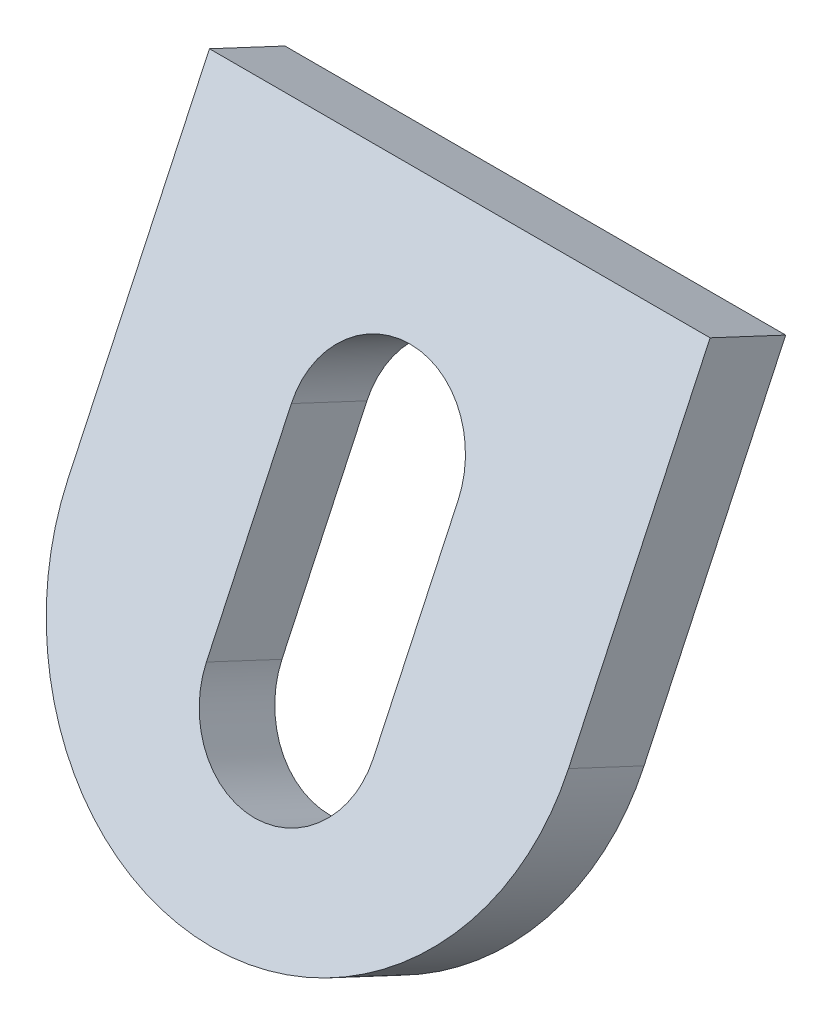
SolidWorks part; units mm, degrees
ref_plane "Front Plane" through (0, 0, 0) normal (0, 0, 1) x (1, 0, 0)
ref_plane "Top Plane" through (0, 0, 0) normal (0, 1, 0) x (1, 0, 0)
ref_plane "Right Plane" through (0, 0, 0) normal (1, 0, 0) x (0, 0, -1)
sketch "Sketch1" plane through (0, 24.053, 51.3381) normal (0, 0.4243, 0.9055) x (1, 0, 0)
  line L0 (-325.7865, 437.5812) -> (325.7865, 437.5812) construction
  line L1 (-223.4896, 437.5812) -> (-204.4396, 437.5812)
  line L2 (-223.4896, 437.5812) -> (-223.4896, 424.8812)
  line L4 (-204.4396, 437.5812) -> (-204.4396, 424.8812)
  line L5 (-210.7896, 422.3412) -> (-210.7896, 429.9612)
  line L6 (-217.1396, 429.9612) -> (-217.1396, 422.3412)
  arc A0 (-223.4896, 424.8812) -> (-204.4396, 424.8812) centre (-213.9646, 424.8812) ccw
  arc A1 (-217.1396, 422.3412) -> (-210.7896, 422.3412) centre (-213.9646, 422.3412) ccw
  arc A2 (-210.7896, 429.9612) -> (-217.1396, 429.9612) centre (-213.9646, 429.9612) ccw
  point P7 (-207.7392, 430.859)
  point P10 (0, 0)
  point P15 (0, 0)
  point P16 (-213.9646, 437.5812)
  point P17 (0, 0)
  dimension "D3" = 6.35
  dimension "D4" = 9.525
  dimension "D1" = 19.05
  dimension "D2" = 12.7
  dimension "D5" = 7.62
  dimension "D6" = 7.62
  dimension "D7" = 101.6
extrude "Boss-Extrude1" add sketch "Sketch1" along normal blind 3.175
